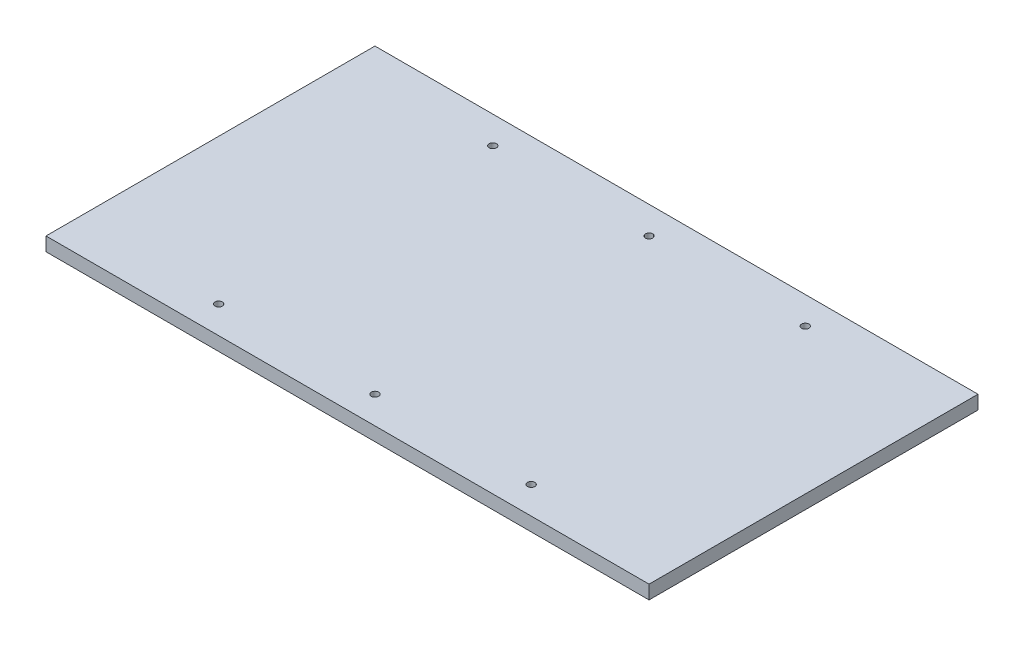
SolidWorks part; units mm, degrees
material "Acrylic (Medium-high impact)"
ref_plane "Front Plane" through (0, 0, 0) normal (0, 0, 1) x (1, 0, 0)
ref_plane "Top Plane" through (0, 0, 0) normal (0, 1, 0) x (1, 0, 0)
ref_plane "Right Plane" through (0, 0, 0) normal (1, 0, 0) x (0, 0, -1)
sketch "Sketch1" plane through (0, 0, 0) normal (0, 1, 0) x (1, 0, 0)
  line L0 (0, 0) -> (0, 74.295) construction
  line L1 (-89.535, 63.5) -> (-55.245, 63.5) construction
  line L2 (139.7, -76.2) -> (-139.7, -76.2)
  line L3 (139.7, -76.2) -> (139.7, 76.2)
  line L4 (139.7, 76.2) -> (-139.7, 76.2)
  line L5 (-139.7, -76.2) -> (-139.7, 76.2)
  line L6 (139.7, -76.2) -> (-139.7, 76.2) construction
  line L7 (139.7, 76.2) -> (-139.7, -76.2) construction
  line L8 (-127.635, 63.5) -> (-89.535, 63.5) construction
  line L9 (-127.635, 63.5) -> (-127.635, -63.5) construction
  line L10 (-127.635, -63.5) -> (-89.535, -63.5) construction
  line L11 (-89.535, 63.5) -> (-89.535, -63.5) construction
  line L12 (-55.245, 63.5) -> (-17.145, 63.5) construction
  line L13 (-55.245, 63.5) -> (-55.245, -63.5) construction
  line L14 (-55.245, -63.5) -> (-17.145, -63.5) construction
  line L15 (-17.145, 63.5) -> (-17.145, -63.5) construction
  line L16 (17.145, 63.5) -> (55.245, 63.5) construction
  line L17 (17.145, 63.5) -> (17.145, -63.5) construction
  line L18 (17.145, -63.5) -> (55.245, -63.5) construction
  line L19 (55.245, 63.5) -> (55.245, -63.5) construction
  line L20 (89.535, 63.5) -> (127.635, 63.5) construction
  line L21 (89.535, 63.5) -> (89.535, -63.5) construction
  line L22 (89.535, -63.5) -> (127.635, -63.5) construction
  line L23 (127.635, 63.5) -> (127.635, -63.5) construction
  line L24 (-17.145, 63.5) -> (17.145, 63.5) construction
  line L25 (55.245, 63.5) -> (89.535, 63.5) construction
  line L26 (-17.145, 0) -> (17.145, 0) construction
  line L27 (-130.175, 44.45) -> (-137.16, 44.45) construction
  line L28 (-137.16, 44.45) -> (-137.16, 74.295) construction
  line L29 (-137.16, 74.295) -> (137.16, 74.295) construction
  line L30 (137.16, 74.295) -> (137.16, 44.45) construction
  line L31 (137.16, 44.45) -> (130.175, 44.45) construction
  line L32 (130.175, 44.45) -> (130.175, 64.77) construction
  line L33 (130.175, 64.77) -> (86.995, 64.77) construction
  line L34 (86.995, 64.77) -> (86.995, 44.45) construction
  line L35 (86.995, 44.45) -> (57.785, 44.45) construction
  line L36 (57.785, 44.45) -> (57.785, 64.77) construction
  line L37 (57.785, 64.77) -> (14.605, 64.77) construction
  line L38 (14.605, 64.77) -> (14.605, 44.45) construction
  line L39 (14.605, 44.45) -> (-14.605, 44.45) construction
  line L40 (-14.605, 44.45) -> (-14.605, 64.77) construction
  line L41 (-14.605, 64.77) -> (-57.785, 64.77) construction
  line L42 (-57.785, 64.77) -> (-57.785, 44.45) construction
  line L43 (-57.785, 44.45) -> (-86.995, 44.45) construction
  line L44 (-86.995, 44.45) -> (-86.995, 64.77) construction
  line L45 (-86.995, 64.77) -> (-130.175, 64.77) construction
  line L46 (-130.175, 64.77) -> (-130.175, 44.45) construction
  line L47 (-137.16, 74.295) -> (-139.7, 74.295) construction
  line L48 (0, 63.5) -> (0, 44.45) construction
  line L49 (-72.39, 44.45) -> (-72.39, 63.5) construction
  line L50 (72.39, 63.5) -> (72.39, 44.45) construction
  circle A0 centre (-72.39, 63.5) radius 1.7
  circle A1 centre (72.39, -63.5) radius 1.7
  circle A2 centre (0, 63.5) radius 1.7
  circle A3 centre (72.39, 63.5) radius 1.7
  circle A4 centre (0, -63.5) radius 1.7
  circle A5 centre (-72.39, -63.5) radius 1.7
  point P23 (-17.145, 0)
  point P24 (17.145, 0)
  point P27 (0, 0)
  dimension "D19" = 3.4
  dimension "D2" = 127
  dimension "D3" = 38.1
  dimension "D4" = 6.985
  dimension "D5" = 279.4
  dimension "D6" = 19.05
  dimension "D7" = 2.54
  dimension "D8" = 2.54
  dimension "D9" = 2.54
  dimension "D10" = 2.54
  dimension "D11" = 2.54
  dimension "D15" = 2.54
  dimension "D17" = 9.525
  dimension "D18" = 2.54
extrude "Boss-Extrude1" add sketch "Sketch1" along normal blind 6.35
